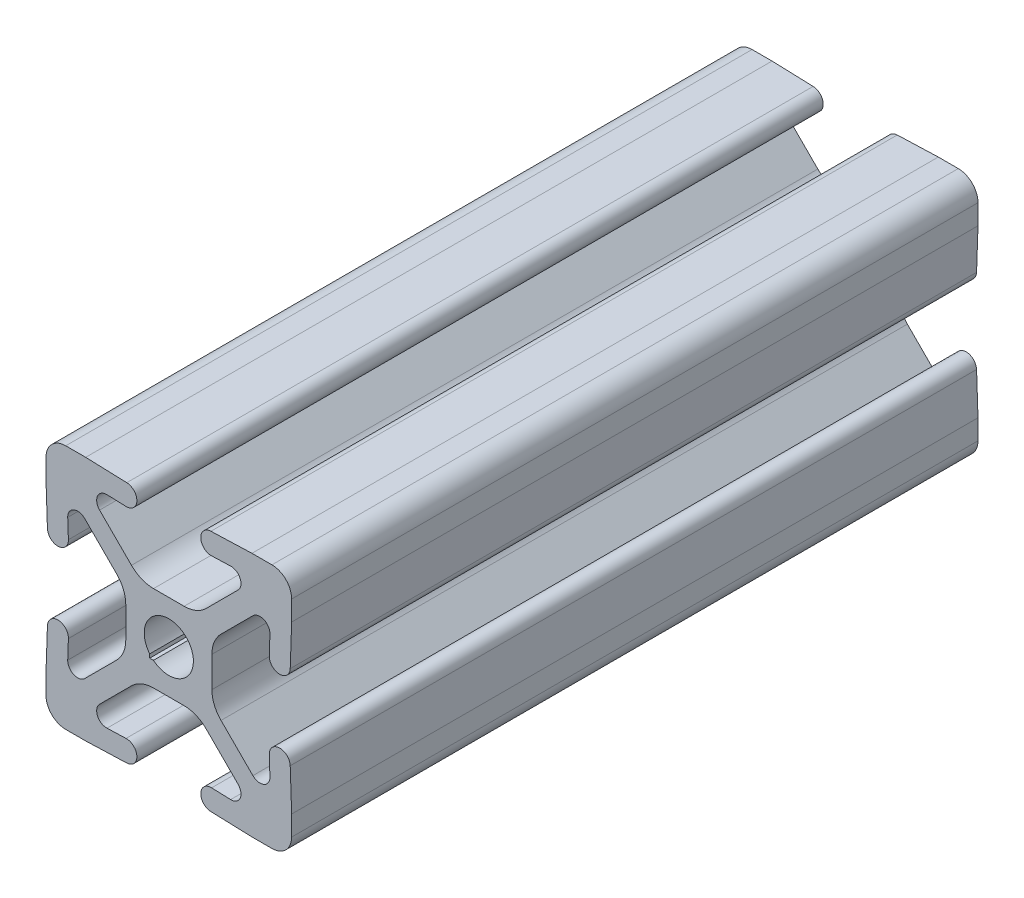
SolidWorks part; units mm, degrees
ref_plane "Front Plane" through (0, 0, 0) normal (0, 0, 1) x (1, 0, 0)
ref_plane "Top Plane" through (0, 0, 0) normal (0, 1, 0) x (1, 0, 0)
ref_plane "Right Plane" through (0, 0, 0) normal (1, 0, 0) x (0, 0, -1)
sketch "Model" plane through (0, 0, 0) normal (0, 0, 1) x (1, 0, 0)
  line L38 (50.6495, 75.4336) -> (50.2699, 75.4336)
  line L39 (50.2699, 75.4336) -> (50.2699, 75.8133)
  line L40 (50.66, 72.9999) -> (53.7746, 72.9999)
  line L41 (56.0196, 72.0699) -> (59.2642, 68.8254)
  line L42 (58.5103, 67.0916) -> (56.5725, 67.1592)
  line L43 (56.498, 65.0269) -> (60.6773, 64.881)
  line L44 (60.6773, 64.881) -> (62.7107, 64.881)
  line L45 (64.7173, 66.8876) -> (64.7173, 68.921)
  line L46 (64.7173, 68.921) -> (64.5713, 73.1002)
  line L47 (62.439, 73.0257) -> (62.5067, 71.0879)
  line L48 (60.7729, 70.334) -> (57.5283, 73.5786)
  line L49 (56.5984, 75.8237) -> (56.5984, 78.9383)
  line L50 (57.5283, 81.1833) -> (60.7729, 84.4279)
  line L51 (62.5067, 83.674) -> (62.439, 81.7362)
  line L52 (64.5713, 81.6617) -> (64.7173, 85.841)
  line L53 (64.7173, 85.841) -> (64.7173, 87.8744)
  line L54 (62.7107, 89.881) -> (60.6773, 89.881)
  line L55 (60.6773, 89.881) -> (56.498, 89.735)
  line L56 (56.5725, 87.6027) -> (58.5103, 87.6704)
  line L57 (59.2642, 85.9366) -> (56.0196, 82.692)
  line L58 (53.7746, 81.7621) -> (50.66, 81.7621)
  line L59 (48.4149, 82.692) -> (45.1703, 85.9366)
  line L60 (45.9242, 87.6704) -> (47.862, 87.6027)
  line L61 (47.9365, 89.735) -> (43.7573, 89.881)
  line L62 (43.7573, 89.881) -> (41.7239, 89.881)
  line L63 (39.7173, 87.8744) -> (39.7173, 85.841)
  line L64 (39.7173, 85.841) -> (39.8632, 81.6617)
  line L65 (41.9955, 81.7362) -> (41.9278, 83.674)
  line L66 (43.6616, 84.4279) -> (46.9062, 81.1833)
  line L67 (47.8361, 78.9383) -> (47.8361, 75.8237)
  line L68 (46.9062, 73.5786) -> (43.6616, 70.334)
  line L69 (41.9278, 71.0879) -> (41.9955, 73.0257)
  line L70 (39.8632, 73.1002) -> (39.7173, 68.921)
  line L71 (39.7173, 68.921) -> (39.7173, 66.8876)
  line L72 (41.7239, 64.881) -> (43.7573, 64.881)
  line L73 (43.7573, 64.881) -> (47.9365, 65.0269)
  line L74 (47.862, 67.1592) -> (45.9242, 67.0916)
  line L75 (45.1703, 68.8254) -> (48.4149, 72.0699)
  arc A29 (50.6495, 75.4336) -> (50.2699, 75.8133) centre (52.2173, 77.381) ccw
  arc A30 (56.0196, 72.0699) -> (53.7746, 72.9999) centre (53.7746, 69.8249) ccw
  arc A31 (58.5103, 67.0916) -> (59.2642, 68.8254) centre (58.5458, 68.1069) ccw
  arc A32 (56.5725, 67.1592) -> (56.498, 65.0269) centre (56.5353, 66.0931) ccw
  arc A33 (62.7107, 64.881) -> (64.7173, 66.8876) centre (62.7107, 66.8876) ccw
  arc A34 (64.5713, 73.1002) -> (62.439, 73.0257) centre (63.5052, 73.063) ccw
  arc A35 (60.7729, 70.334) -> (62.5067, 71.0879) centre (61.4913, 71.0525) ccw
  arc A36 (56.5984, 75.8237) -> (57.5283, 73.5786) centre (59.7734, 75.8237) ccw
  arc A37 (57.5283, 81.1833) -> (56.5984, 78.9383) centre (59.7734, 78.9383) ccw
  arc A38 (62.5067, 83.674) -> (60.7729, 84.4279) centre (61.4913, 83.7095) ccw
  arc A39 (62.439, 81.7362) -> (64.5713, 81.6617) centre (63.5052, 81.699) ccw
  arc A40 (64.7173, 87.8744) -> (62.7107, 89.881) centre (62.7107, 87.8744) ccw
  arc A41 (56.498, 89.735) -> (56.5725, 87.6027) centre (56.5353, 88.6689) ccw
  arc A42 (59.2642, 85.9366) -> (58.5103, 87.6704) centre (58.5458, 86.655) ccw
  arc A43 (53.7746, 81.7621) -> (56.0196, 82.692) centre (53.7746, 84.9371) ccw
  arc A44 (48.4149, 82.692) -> (50.66, 81.7621) centre (50.66, 84.9371) ccw
  arc A45 (45.9242, 87.6704) -> (45.1703, 85.9366) centre (45.8887, 86.655) ccw
  arc A46 (47.862, 87.6027) -> (47.9365, 89.735) centre (47.8993, 88.6689) ccw
  arc A47 (41.7239, 89.881) -> (39.7173, 87.8744) centre (41.7239, 87.8744) ccw
  arc A48 (39.8632, 81.6617) -> (41.9955, 81.7362) centre (40.9293, 81.699) ccw
  arc A49 (43.6616, 84.4279) -> (41.9278, 83.674) centre (42.9432, 83.7095) ccw
  arc A50 (47.8361, 78.9383) -> (46.9062, 81.1833) centre (44.6611, 78.9383) ccw
  arc A51 (46.9062, 73.5786) -> (47.8361, 75.8237) centre (44.6611, 75.8237) ccw
  arc A52 (41.9278, 71.0879) -> (43.6616, 70.334) centre (42.9432, 71.0525) ccw
  arc A53 (41.9955, 73.0257) -> (39.8632, 73.1002) centre (40.9293, 73.063) ccw
  arc A54 (39.7173, 66.8876) -> (41.7239, 64.881) centre (41.7239, 66.8876) ccw
  arc A55 (47.9365, 65.0269) -> (47.862, 67.1592) centre (47.8993, 66.0931) ccw
  arc A56 (45.1703, 68.8254) -> (45.9242, 67.0916) centre (45.8887, 68.1069) ccw
  arc A57 (50.66, 72.9999) -> (48.4149, 72.0699) centre (50.66, 69.8249) ccw
extrude "Boss-Extrude1" add sketch "Model" along normal blind 69.85
